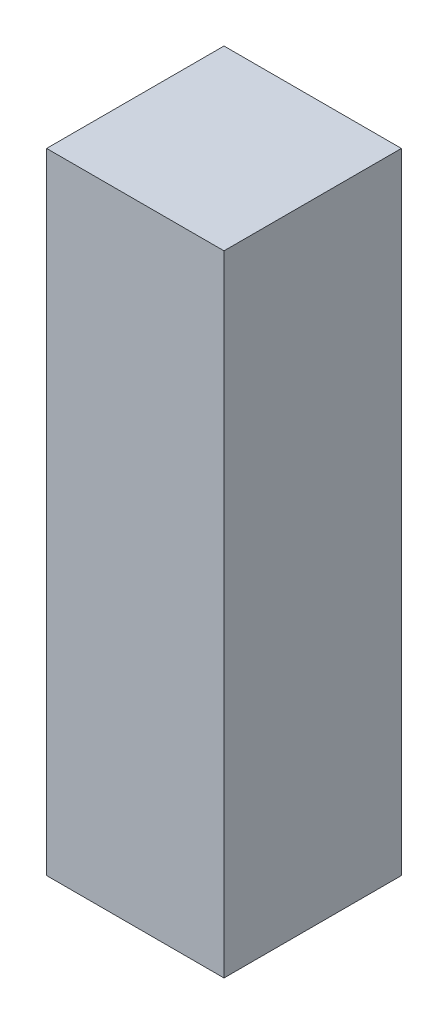
SolidWorks part; units mm, degrees
ref_plane "前视基准面" through (0, 0, 0) normal (0, 0, 1) x (1, 0, 0)
ref_plane "上视基准面" through (0, 0, 0) normal (0, 1, 0) x (1, 0, 0)
ref_plane "右视基准面" through (0, 0, 0) normal (1, 0, 0) x (0, 0, -1)
other "Configuration Table"
sketch "草图1" plane through (0, 0, 0) normal (0, 1, 0) x (1, 0, 0)
  line L1 (0, 0) -> (5, 0)
  line L2 (0, 0) -> (0, 5)
  line L3 (0, 5) -> (5, 5)
  line L4 (5, 0) -> (5, 5)
  dimension "D1" = 5
  dimension "D2" = 5
extrude "凸台-拉伸1" add sketch "草图1" along normal blind 17.75
